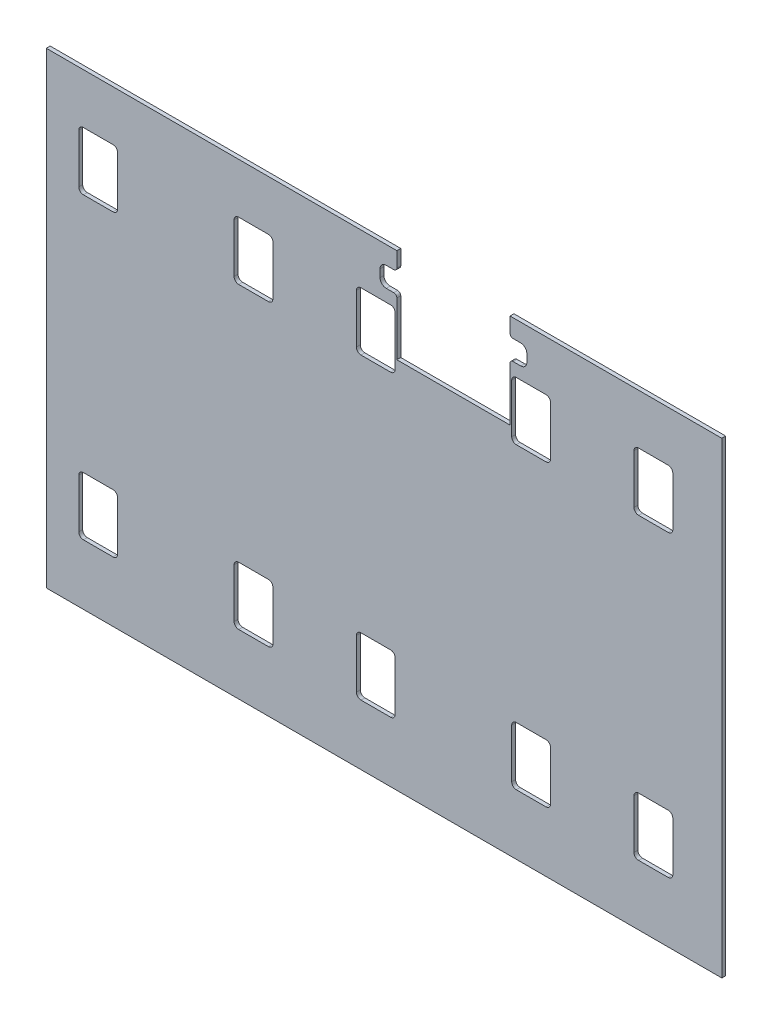
SolidWorks part; units mm, degrees
material "PP Film"
ref_plane "X-Y Datum" through (0, 0, 0) normal (0, 0, 1) x (1, 0, 0)
ref_plane "X-Z Datum" through (0, 0, 0) normal (0, 1, 0) x (1, 0, 0)
ref_plane "Y-Z Datum" through (0, 0, 0) normal (1, 0, 0) x (0, 0, -1)
sketch "Sketch1" plane through (0, 0, 0) normal (0, 0, 1) x (1, 0, 0)
  line L0 (-177.3154, 116.8) -> (-196.7154, 116.8) construction
  line L1 (-199.7154, 113.8) -> (-199.7154, 81.7) construction
  line L2 (-174.3154, 81.7) -> (-174.3154, 113.8) construction
  line L3 (-196.7154, 78.7) -> (-177.3154, 78.7) construction
  line L4 (-220.9897, 149.5877) -> (-220.9897, -156.2291)
  line L5 (-220.9897, -156.2291) -> (220.9897, -156.2291)
  line L6 (220.9897, -156.2291) -> (220.9897, 149.5877)
  line L7 (220.9897, 149.5877) -> (-220.9897, 149.5877)
  line L8 (-220.9897, 149.5877) -> (-220.9897, -156.2291)
  line L9 (-220.9897, -156.2291) -> (220.9897, -156.2291)
  line L10 (220.9897, -156.2291) -> (220.9897, 149.5877)
  line L11 (220.9897, 149.5877) -> (-220.9897, 149.5877)
  line L12 (-177.3154, 116.8) -> (-196.7154, 116.8)
  line L13 (-199.7154, 113.8) -> (-199.7154, 81.7)
  line L14 (-174.3154, 81.7) -> (-174.3154, 113.8)
  line L15 (-196.7154, 78.7) -> (-177.3154, 78.7)
  line L16 (-174.3154, -81.7) -> (-174.3154, -113.8) construction
  line L18 (-196.7154, -78.7) -> (-177.3154, -78.7) construction
  line L19 (-199.7154, -113.8) -> (-199.7154, -81.7) construction
  line L20 (-177.3154, -116.8) -> (-196.7154, -116.8) construction
  line L21 (-199.7154, -113.8) -> (-199.7154, -81.7)
  line L22 (-196.7154, -78.7) -> (-177.3154, -78.7)
  line L23 (-174.3154, -81.7) -> (-174.3154, -113.8)
  line L24 (-177.3154, -116.8) -> (-196.7154, -116.8)
  line L25 (-75.7126, 116.8) -> (-95.1126, 116.8) construction
  line L26 (-95.1126, 78.7) -> (-75.7126, 78.7) construction
  line L27 (-98.1126, 113.8) -> (-98.1126, 81.7) construction
  line L28 (-72.7126, 81.7) -> (-72.7126, 113.8) construction
  line L29 (-75.7126, 116.8) -> (-95.1126, 116.8)
  line L30 (-95.1126, 78.7) -> (-75.7126, 78.7)
  line L31 (-98.1126, 113.8) -> (-98.1126, 81.7)
  line L32 (-72.7126, 81.7) -> (-72.7126, 113.8)
  line L33 (-95.1126, -78.7) -> (-75.7126, -78.7) construction
  line L34 (-72.7126, -81.7) -> (-72.7126, -113.8) construction
  line L35 (-98.1126, -113.8) -> (-98.1126, -81.7) construction
  line L36 (-75.7126, -116.8) -> (-95.1126, -116.8) construction
  line L37 (-95.1126, -78.7) -> (-75.7126, -78.7)
  line L38 (-72.7126, -81.7) -> (-72.7126, -113.8)
  line L39 (-98.1126, -113.8) -> (-98.1126, -81.7)
  line L40 (-75.7126, -116.8) -> (-95.1126, -116.8)
  arc A0 (-174.3154, 113.8) -> (-177.3154, 116.8) centre (-177.3154, 113.8) ccw construction
  arc A1 (-196.7154, 116.8) -> (-199.7154, 113.8) centre (-196.7154, 113.8) ccw construction
  arc A2 (-177.3154, 78.7) -> (-174.3154, 81.7) centre (-177.3154, 81.7) ccw construction
  arc A3 (-199.7154, 81.7) -> (-196.7154, 78.7) centre (-196.7154, 81.7) ccw construction
  arc A4 (-174.3154, 113.8) -> (-177.3154, 116.8) centre (-177.3154, 113.8) ccw
  arc A5 (-196.7154, 116.8) -> (-199.7154, 113.8) centre (-196.7154, 113.8) ccw
  arc A6 (-177.3154, 78.7) -> (-174.3154, 81.7) centre (-177.3154, 81.7) ccw
  arc A7 (-199.7154, 81.7) -> (-196.7154, 78.7) centre (-196.7154, 81.7) ccw
  arc A8 (-174.3154, -81.7) -> (-177.3154, -78.7) centre (-177.3154, -81.7) ccw construction
  arc A9 (-196.7154, -78.7) -> (-199.7154, -81.7) centre (-196.7154, -81.7) ccw construction
  arc A10 (-177.3154, -116.8) -> (-174.3154, -113.8) centre (-177.3154, -113.8) ccw construction
  arc A11 (-199.7154, -113.8) -> (-196.7154, -116.8) centre (-196.7154, -113.8) ccw construction
  arc A12 (-196.7154, -78.7) -> (-199.7154, -81.7) centre (-196.7154, -81.7) ccw
  arc A13 (-174.3154, -81.7) -> (-177.3154, -78.7) centre (-177.3154, -81.7) ccw
  arc A14 (-177.3154, -116.8) -> (-174.3154, -113.8) centre (-177.3154, -113.8) ccw
  arc A15 (-199.7154, -113.8) -> (-196.7154, -116.8) centre (-196.7154, -113.8) ccw
  arc A16 (-72.7126, 113.8) -> (-75.7126, 116.8) centre (-75.7126, 113.8) ccw construction
  arc A17 (-95.1126, 116.8) -> (-98.1126, 113.8) centre (-95.1126, 113.8) ccw construction
  arc A18 (-75.7126, 78.7) -> (-72.7126, 81.7) centre (-75.7126, 81.7) ccw construction
  arc A19 (-98.1126, 81.7) -> (-95.1126, 78.7) centre (-95.1126, 81.7) ccw construction
  arc A20 (-72.7126, 113.8) -> (-75.7126, 116.8) centre (-75.7126, 113.8) ccw
  arc A21 (-95.1126, 116.8) -> (-98.1126, 113.8) centre (-95.1126, 113.8) ccw
  arc A22 (-75.7126, 78.7) -> (-72.7126, 81.7) centre (-75.7126, 81.7) ccw
  arc A23 (-98.1126, 81.7) -> (-95.1126, 78.7) centre (-95.1126, 81.7) ccw
  arc A24 (-72.7126, -81.7) -> (-75.7126, -78.7) centre (-75.7126, -81.7) ccw construction
  arc A25 (-95.1126, -78.7) -> (-98.1126, -81.7) centre (-95.1126, -81.7) ccw construction
  arc A26 (-75.7126, -116.8) -> (-72.7126, -113.8) centre (-75.7126, -113.8) ccw construction
  arc A27 (-98.1126, -113.8) -> (-95.1126, -116.8) centre (-95.1126, -113.8) ccw construction
  arc A28 (-72.7126, -81.7) -> (-75.7126, -78.7) centre (-75.7126, -81.7) ccw
  arc A29 (-95.1126, -78.7) -> (-98.1126, -81.7) centre (-95.1126, -81.7) ccw
  arc A30 (-75.7126, -116.8) -> (-72.7126, -113.8) centre (-75.7126, -113.8) ccw
  arc A31 (-98.1126, -113.8) -> (-95.1126, -116.8) centre (-95.1126, -113.8) ccw
  dimension "D1" = 0
extrude "Boss-Extrude1" add sketch "Sketch1" along normal blind 2.54 contours L10 L11 L8 L9 A31 L39 A29 L37 A28 L38 A30 L40 A23 L31 A21 L29 A20 L32 A22 L30 A15 L21 A12 L22 A13 L23 A14 L24 A7 L13 A5 L12 A4 L14 A6 L15 | L21 A15 L24 A14 L23 A13 L22 A12 | L39 A31 L40 A30 L38 A28 L37 A29 | L13 A7 L15 A6 L14 A4 L12 A5 | L31 A23 L30 A22 L32 A20 L29 A21
sketch "Sketch2" plane through (0, 0, 2.54) normal (0, 0, 1) x (1, 0, 0)
  line L4 (-220.9897, 149.5877) -> (-220.9897, -156.2291)
  line L5 (-220.9897, -156.2291) -> (220.9897, -156.2291)
  line L6 (220.9897, -156.2291) -> (220.9897, 149.5877)
  line L7 (220.9897, 149.5877) -> (-220.9897, 149.5877)
  line L8 (-220.9897, 149.5877) -> (-220.9897, -156.2291)
  line L9 (-220.9897, -156.2291) -> (220.9897, -156.2291)
  line L10 (220.9897, -156.2291) -> (220.9897, 149.5877)
  line L11 (220.9897, 149.5877) -> (-220.9897, 149.5877)
  line L12 (-199.7154, -81.7) -> (-199.7154, -113.8)
  line L13 (-177.3154, -78.7) -> (-196.7154, -78.7)
  line L14 (-174.3154, -113.8) -> (-174.3154, -81.7)
  line L15 (-196.7154, -116.8) -> (-177.3154, -116.8)
  line L16 (-199.7154, -81.7) -> (-199.7154, -113.8)
  line L17 (-177.3154, -78.7) -> (-196.7154, -78.7)
  line L18 (-174.3154, -113.8) -> (-174.3154, -81.7)
  line L19 (-196.7154, -116.8) -> (-177.3154, -116.8)
  line L20 (-199.7154, 113.8) -> (-199.7154, 81.7)
  line L21 (-177.3154, 116.8) -> (-196.7154, 116.8)
  line L22 (-174.3154, 81.7) -> (-174.3154, 113.8)
  line L23 (-196.7154, 78.7) -> (-177.3154, 78.7)
  line L24 (-199.7154, 113.8) -> (-199.7154, 81.7)
  line L25 (-177.3154, 116.8) -> (-196.7154, 116.8)
  line L26 (-174.3154, 81.7) -> (-174.3154, 113.8)
  line L27 (-196.7154, 78.7) -> (-177.3154, 78.7)
  line L28 (-75.7126, 116.8) -> (-95.1126, 116.8)
  line L29 (-72.7126, 81.7) -> (-72.7126, 113.8)
  line L30 (-95.1126, 78.7) -> (-75.7126, 78.7)
  line L31 (-98.1126, 113.8) -> (-98.1126, 81.7)
  line L32 (-75.7126, 116.8) -> (-95.1126, 116.8)
  line L33 (-72.7126, 81.7) -> (-72.7126, 113.8)
  line L34 (-95.1126, 78.7) -> (-75.7126, 78.7)
  line L35 (-98.1126, 113.8) -> (-98.1126, 81.7)
  line L36 (-95.1126, -116.8) -> (-75.7126, -116.8)
  line L37 (-72.7126, -113.8) -> (-72.7126, -81.7)
  line L38 (-75.7126, -78.7) -> (-95.1126, -78.7)
  line L39 (-98.1126, -81.7) -> (-98.1126, -113.8)
  line L40 (-95.1126, -116.8) -> (-75.7126, -116.8)
  line L41 (-72.7126, -113.8) -> (-72.7126, -81.7)
  line L42 (-75.7126, -78.7) -> (-95.1126, -78.7)
  line L43 (-98.1126, -81.7) -> (-98.1126, -113.8)
  arc A4 (-196.7154, -78.7) -> (-199.7154, -81.7) centre (-196.7154, -81.7) ccw
  arc A5 (-174.3154, -81.7) -> (-177.3154, -78.7) centre (-177.3154, -81.7) ccw
  arc A6 (-177.3154, -116.8) -> (-174.3154, -113.8) centre (-177.3154, -113.8) ccw
  arc A7 (-199.7154, -113.8) -> (-196.7154, -116.8) centre (-196.7154, -113.8) ccw
  arc A8 (-196.7154, -78.7) -> (-199.7154, -81.7) centre (-196.7154, -81.7) ccw
  arc A9 (-174.3154, -81.7) -> (-177.3154, -78.7) centre (-177.3154, -81.7) ccw
  arc A10 (-177.3154, -116.8) -> (-174.3154, -113.8) centre (-177.3154, -113.8) ccw
  arc A11 (-199.7154, -113.8) -> (-196.7154, -116.8) centre (-196.7154, -113.8) ccw
  arc A12 (-199.7154, 81.7) -> (-196.7154, 78.7) centre (-196.7154, 81.7) ccw
  arc A13 (-196.7154, 116.8) -> (-199.7154, 113.8) centre (-196.7154, 113.8) ccw
  arc A14 (-174.3154, 113.8) -> (-177.3154, 116.8) centre (-177.3154, 113.8) ccw
  arc A15 (-177.3154, 78.7) -> (-174.3154, 81.7) centre (-177.3154, 81.7) ccw
  arc A16 (-199.7154, 81.7) -> (-196.7154, 78.7) centre (-196.7154, 81.7) ccw
  arc A17 (-196.7154, 116.8) -> (-199.7154, 113.8) centre (-196.7154, 113.8) ccw
  arc A18 (-174.3154, 113.8) -> (-177.3154, 116.8) centre (-177.3154, 113.8) ccw
  arc A19 (-177.3154, 78.7) -> (-174.3154, 81.7) centre (-177.3154, 81.7) ccw
  arc A20 (-72.7126, 113.8) -> (-75.7126, 116.8) centre (-75.7126, 113.8) ccw
  arc A21 (-75.7126, 78.7) -> (-72.7126, 81.7) centre (-75.7126, 81.7) ccw
  arc A22 (-98.1126, 81.7) -> (-95.1126, 78.7) centre (-95.1126, 81.7) ccw
  arc A23 (-95.1126, 116.8) -> (-98.1126, 113.8) centre (-95.1126, 113.8) ccw
  arc A24 (-72.7126, 113.8) -> (-75.7126, 116.8) centre (-75.7126, 113.8) ccw
  arc A25 (-75.7126, 78.7) -> (-72.7126, 81.7) centre (-75.7126, 81.7) ccw
  arc A26 (-98.1126, 81.7) -> (-95.1126, 78.7) centre (-95.1126, 81.7) ccw
  arc A27 (-95.1126, 116.8) -> (-98.1126, 113.8) centre (-95.1126, 113.8) ccw
  arc A28 (-98.1126, -113.8) -> (-95.1126, -116.8) centre (-95.1126, -113.8) ccw
  arc A29 (-75.7126, -116.8) -> (-72.7126, -113.8) centre (-75.7126, -113.8) ccw
  arc A30 (-72.7126, -81.7) -> (-75.7126, -78.7) centre (-75.7126, -81.7) ccw
  arc A31 (-95.1126, -78.7) -> (-98.1126, -81.7) centre (-95.1126, -81.7) ccw
  arc A32 (-98.1126, -113.8) -> (-95.1126, -116.8) centre (-95.1126, -113.8) ccw
  arc A33 (-75.7126, -116.8) -> (-72.7126, -113.8) centre (-75.7126, -113.8) ccw
  arc A34 (-72.7126, -81.7) -> (-75.7126, -78.7) centre (-75.7126, -81.7) ccw
  arc A35 (-95.1126, -78.7) -> (-98.1126, -81.7) centre (-95.1126, -81.7) ccw
  dimension "D1" = 0
  dimension "D2" = 0
  dimension "D3" = 0
  dimension "D4" = 0
  dimension "D5" = 0
extrude "Cut-Extrude1" cut sketch "Sketch2" against normal through all contours L27 A19 L26 A18 L25 A17 L24 A16 | L16 A11 L19 A10 L18 A9 L17 A8
pattern_linear "LPattern1" count 3 spacing 181.614 along (1, 0, 0) of "Cut-Extrude1"
sketch "Sketch3" plane through (0, 0, 2.54) normal (0, 0, 1) x (1, 0, 0)
  line L4 (-220.9897, 149.5877) -> (-220.9897, -156.2291)
  line L5 (-220.9897, -156.2291) -> (220.9897, -156.2291)
  line L6 (220.9897, -156.2291) -> (220.9897, 149.5877)
  line L7 (220.9897, 149.5877) -> (-220.9897, 149.5877)
  line L8 (-220.9897, 149.5877) -> (-220.9897, -156.2291)
  line L9 (-220.9897, -156.2291) -> (220.9897, -156.2291)
  line L10 (220.9897, -156.2291) -> (220.9897, 149.5877)
  line L11 (220.9897, 149.5877) -> (-220.9897, 149.5877)
  line L12 (-196.7154, -116.8) -> (-177.3154, -116.8)
  line L13 (-174.3154, -113.8) -> (-174.3154, -81.7)
  line L14 (-177.3154, -78.7) -> (-196.7154, -78.7)
  line L15 (-199.7154, -81.7) -> (-199.7154, -113.8)
  line L16 (-196.7154, -116.8) -> (-177.3154, -116.8)
  line L17 (-174.3154, -113.8) -> (-174.3154, -81.7)
  line L18 (-177.3154, -78.7) -> (-196.7154, -78.7)
  line L19 (-199.7154, -81.7) -> (-199.7154, -113.8)
  line L20 (-95.1126, 78.7) -> (-75.7126, 78.7)
  line L21 (-98.1126, 113.8) -> (-98.1126, 81.7)
  line L22 (-75.7126, 116.8) -> (-95.1126, 116.8)
  line L23 (-72.7126, 81.7) -> (-72.7126, 113.8)
  line L24 (-95.1126, 78.7) -> (-75.7126, 78.7)
  line L25 (-98.1126, 113.8) -> (-98.1126, 81.7)
  line L26 (-75.7126, 116.8) -> (-95.1126, 116.8)
  line L27 (-72.7126, 81.7) -> (-72.7126, 113.8)
  line L28 (-196.7154, 78.7) -> (-177.3154, 78.7)
  line L29 (-199.7154, 113.8) -> (-199.7154, 81.7)
  line L30 (-177.3154, 116.8) -> (-196.7154, 116.8)
  line L31 (-174.3154, 81.7) -> (-174.3154, 113.8)
  line L32 (-196.7154, 78.7) -> (-177.3154, 78.7)
  line L33 (-199.7154, 113.8) -> (-199.7154, 81.7)
  line L34 (-177.3154, 116.8) -> (-196.7154, 116.8)
  line L35 (-174.3154, 81.7) -> (-174.3154, 113.8)
  line L36 (-72.7126, -113.8) -> (-72.7126, -81.7)
  line L37 (-95.1126, -116.8) -> (-75.7126, -116.8)
  line L38 (-98.1126, -81.7) -> (-98.1126, -113.8)
  line L39 (-75.7126, -78.7) -> (-95.1126, -78.7)
  line L40 (-72.7126, -113.8) -> (-72.7126, -81.7)
  line L41 (-95.1126, -116.8) -> (-75.7126, -116.8)
  line L42 (-98.1126, -81.7) -> (-98.1126, -113.8)
  line L43 (-75.7126, -78.7) -> (-95.1126, -78.7)
  arc A4 (-177.3154, -116.8) -> (-174.3154, -113.8) centre (-177.3154, -113.8) ccw
  arc A5 (-174.3154, -81.7) -> (-177.3154, -78.7) centre (-177.3154, -81.7) ccw
  arc A6 (-196.7154, -78.7) -> (-199.7154, -81.7) centre (-196.7154, -81.7) ccw
  arc A7 (-199.7154, -113.8) -> (-196.7154, -116.8) centre (-196.7154, -113.8) ccw
  arc A8 (-177.3154, -116.8) -> (-174.3154, -113.8) centre (-177.3154, -113.8) ccw
  arc A9 (-174.3154, -81.7) -> (-177.3154, -78.7) centre (-177.3154, -81.7) ccw
  arc A10 (-196.7154, -78.7) -> (-199.7154, -81.7) centre (-196.7154, -81.7) ccw
  arc A11 (-199.7154, -113.8) -> (-196.7154, -116.8) centre (-196.7154, -113.8) ccw
  arc A12 (-75.7126, 78.7) -> (-72.7126, 81.7) centre (-75.7126, 81.7) ccw
  arc A13 (-98.1126, 81.7) -> (-95.1126, 78.7) centre (-95.1126, 81.7) ccw
  arc A14 (-95.1126, 116.8) -> (-98.1126, 113.8) centre (-95.1126, 113.8) ccw
  arc A15 (-72.7126, 113.8) -> (-75.7126, 116.8) centre (-75.7126, 113.8) ccw
  arc A16 (-75.7126, 78.7) -> (-72.7126, 81.7) centre (-75.7126, 81.7) ccw
  arc A17 (-98.1126, 81.7) -> (-95.1126, 78.7) centre (-95.1126, 81.7) ccw
  arc A18 (-95.1126, 116.8) -> (-98.1126, 113.8) centre (-95.1126, 113.8) ccw
  arc A19 (-72.7126, 113.8) -> (-75.7126, 116.8) centre (-75.7126, 113.8) ccw
  arc A20 (-199.7154, 81.7) -> (-196.7154, 78.7) centre (-196.7154, 81.7) ccw
  arc A21 (-196.7154, 116.8) -> (-199.7154, 113.8) centre (-196.7154, 113.8) ccw
  arc A22 (-174.3154, 113.8) -> (-177.3154, 116.8) centre (-177.3154, 113.8) ccw
  arc A23 (-177.3154, 78.7) -> (-174.3154, 81.7) centre (-177.3154, 81.7) ccw
  arc A24 (-199.7154, 81.7) -> (-196.7154, 78.7) centre (-196.7154, 81.7) ccw
  arc A25 (-196.7154, 116.8) -> (-199.7154, 113.8) centre (-196.7154, 113.8) ccw
  arc A26 (-174.3154, 113.8) -> (-177.3154, 116.8) centre (-177.3154, 113.8) ccw
  arc A27 (-177.3154, 78.7) -> (-174.3154, 81.7) centre (-177.3154, 81.7) ccw
  arc A28 (-75.7126, -116.8) -> (-72.7126, -113.8) centre (-75.7126, -113.8) ccw
  arc A29 (-98.1126, -113.8) -> (-95.1126, -116.8) centre (-95.1126, -113.8) ccw
  arc A30 (-95.1126, -78.7) -> (-98.1126, -81.7) centre (-95.1126, -81.7) ccw
  arc A31 (-72.7126, -81.7) -> (-75.7126, -78.7) centre (-75.7126, -81.7) ccw
  arc A32 (-75.7126, -116.8) -> (-72.7126, -113.8) centre (-75.7126, -113.8) ccw
  arc A33 (-98.1126, -113.8) -> (-95.1126, -116.8) centre (-95.1126, -113.8) ccw
  arc A34 (-95.1126, -78.7) -> (-98.1126, -81.7) centre (-95.1126, -81.7) ccw
  arc A35 (-72.7126, -81.7) -> (-75.7126, -78.7) centre (-75.7126, -81.7) ccw
  dimension "D1" = 0
  dimension "D2" = 0
  dimension "D3" = 0
  dimension "D4" = 0
  dimension "D5" = 0
extrude "Cut-Extrude2" cut sketch "Sketch3" against normal through all contours L27 A19 L26 A18 L25 A17 L24 A16 | L40 A35 L43 A34 L42 A33 L41 A32
pattern_linear "LPattern2" count 2 spacing 181.614 along (1, 0, 0) of "Cut-Extrude2"
sketch "Sketch5" plane through (0, 0, 2.54) normal (0, 0, 1) x (1, 0, 0)
  line L0 (79.4, 88.7877) -> (81.4, 88.7877) construction
  line L1 (81.4, 88.7877) -> (81.4, 148.7877) construction
  line L2 (81.4, 148.7877) -> (79.4, 148.7877) construction
  line L3 (79.4, 148.7877) -> (79.4, 88.7877) construction
  line L4 (6.4, 136.7877) -> (1.4, 136.7877)
  line L5 (-1.6, 133.7877) -> (-1.6, 128.7877)
  line L6 (1.4, 125.7877) -> (6.4, 125.7877)
  line L7 (9.4, 122.7877) -> (9.4, 139.7877)
  line L8 (6.4, 136.7877) -> (1.4, 136.7877) construction
  line L9 (-1.6, 133.7877) -> (-1.6, 128.7877) construction
  line L10 (1.4, 125.7877) -> (6.4, 125.7877) construction
  line L11 (9.4, 122.7877) -> (9.4, 139.7877) construction
  line L12 (84.4, 125.7877) -> (89.4, 125.7877)
  line L13 (92.4, 128.7877) -> (92.4, 133.7877)
  line L14 (89.4, 136.7877) -> (84.4, 136.7877)
  line L15 (81.4, 139.7877) -> (81.4, 122.7877)
  line L16 (84.4, 125.7877) -> (89.4, 125.7877) construction
  line L17 (92.4, 128.7877) -> (92.4, 133.7877) construction
  line L18 (89.4, 136.7877) -> (84.4, 136.7877) construction
  line L19 (81.4, 139.7877) -> (81.4, 122.7877) construction
  line L20 (11.4, 88.7877) -> (79.4, 88.7877) construction
  line L21 (79.4, 88.7877) -> (79.4, 148.7877) construction
  line L22 (79.4, 148.7877) -> (11.4, 148.7877) construction
  line L23 (11.4, 148.7877) -> (11.4, 88.7877) construction
  line L24 (9.4, 88.7877) -> (11.4, 88.7877) construction
  line L25 (11.4, 88.7877) -> (11.4, 148.7877) construction
  line L26 (11.4, 148.7877) -> (9.4, 148.7877) construction
  line L27 (9.4, 148.7877) -> (9.4, 88.7877) construction
  line L28 (79.4, 88.7877) -> (81.4, 88.7877) construction
  line L29 (81.4, 88.7877) -> (81.4, 148.7877) construction
  line L30 (81.4, 148.7877) -> (79.4, 148.7877) construction
  line L31 (79.4, 148.7877) -> (79.4, 88.7877) construction
  line L32 (11.4, 88.7877) -> (79.4, 88.7877) construction
  line L33 (79.4, 88.7877) -> (79.4, 148.7877) construction
  line L34 (79.4, 148.7877) -> (11.4, 148.7877) construction
  line L35 (11.4, 148.7877) -> (11.4, 88.7877) construction
  line L36 (9.4, 88.7877) -> (11.4, 88.7877) construction
  line L37 (11.4, 88.7877) -> (11.4, 148.7877) construction
  line L38 (11.4, 148.7877) -> (9.4, 148.7877) construction
  line L39 (9.4, 148.7877) -> (9.4, 88.7877) construction
  line L40 (82.416, 149.8037) -> (8.384, 149.8037)
  line L41 (8.384, 149.8037) -> (8.384, 87.7717)
  line L42 (8.384, 87.7717) -> (11.4, 87.7717)
  line L43 (11.4, 87.7717) -> (79.4, 87.7717)
  line L44 (11.4, 88.7877) -> (79.4, 88.7877)
  line L45 (79.4, 88.7877) -> (79.4, 148.7877)
  line L46 (79.4, 148.7877) -> (11.4, 148.7877)
  line L47 (11.4, 148.7877) -> (11.4, 88.7877)
  line L48 (11.4, 88.7877) -> (79.4, 88.7877) construction
  line L49 (79.4, 88.7877) -> (79.4, 148.7877) construction
  line L50 (79.4, 148.7877) -> (11.4, 148.7877) construction
  line L51 (11.4, 148.7877) -> (11.4, 88.7877) construction
  line L52 (79.4, 87.7717) -> (82.416, 87.7717)
  line L53 (82.416, 87.7717) -> (82.416, 149.8037)
  line L54 (84.4, 124.7717) -> (89.4, 124.7717)
  line L55 (93.416, 128.7877) -> (93.416, 133.7877)
  line L56 (89.4, 137.8037) -> (84.4, 137.8037)
  line L57 (1.4, 124.7717) -> (6.4, 124.7717)
  line L58 (-2.616, 133.7877) -> (-2.616, 128.7877)
  line L59 (6.4, 137.8037) -> (1.4, 137.8037)
  line L60 (11.4, 149.8037) -> (8.384, 149.8037) construction
  line L62 (82.416, 87.7717) -> (82.416, 148.7877) construction
  arc A0 (84.4, 124.7717) -> (82.416, 122.7877) centre (84.4, 122.7877) ccw
  arc A1 (89.4, 124.7717) -> (93.416, 128.7877) centre (89.4, 128.7877) ccw
  arc A2 (93.416, 133.7877) -> (89.4, 137.8037) centre (89.4, 133.7877) ccw
  arc A3 (82.416, 139.7877) -> (84.4, 137.8037) centre (84.4, 139.7877) ccw
  arc A4 (1.4, 136.7877) -> (-1.6, 133.7877) centre (1.4, 133.7877) ccw
  arc A5 (-1.6, 128.7877) -> (1.4, 125.7877) centre (1.4, 128.7877) ccw
  arc A6 (9.4, 122.7877) -> (6.4, 125.7877) centre (6.4, 122.7877) ccw
  arc A7 (6.4, 136.7877) -> (9.4, 139.7877) centre (6.4, 139.7877) ccw
  arc A8 (1.4, 136.7877) -> (-1.6, 133.7877) centre (1.4, 133.7877) ccw construction
  arc A9 (-1.6, 128.7877) -> (1.4, 125.7877) centre (1.4, 128.7877) ccw construction
  arc A10 (9.4, 122.7877) -> (6.4, 125.7877) centre (6.4, 122.7877) ccw construction
  arc A11 (6.4, 136.7877) -> (9.4, 139.7877) centre (6.4, 139.7877) ccw construction
  arc A12 (89.4, 125.7877) -> (92.4, 128.7877) centre (89.4, 128.7877) ccw
  arc A13 (92.4, 133.7877) -> (89.4, 136.7877) centre (89.4, 133.7877) ccw
  arc A14 (81.4, 139.7877) -> (84.4, 136.7877) centre (84.4, 139.7877) ccw
  arc A15 (84.4, 125.7877) -> (81.4, 122.7877) centre (84.4, 122.7877) ccw
  arc A16 (89.4, 125.7877) -> (92.4, 128.7877) centre (89.4, 128.7877) ccw construction
  arc A17 (92.4, 133.7877) -> (89.4, 136.7877) centre (89.4, 133.7877) ccw construction
  arc A18 (81.4, 139.7877) -> (84.4, 136.7877) centre (84.4, 139.7877) ccw construction
  arc A19 (84.4, 125.7877) -> (81.4, 122.7877) centre (84.4, 122.7877) ccw construction
  arc A20 (8.384, 122.7877) -> (6.4, 124.7717) centre (6.4, 122.7877) ccw
  arc A21 (-2.616, 128.7877) -> (1.4, 124.7717) centre (1.4, 128.7877) ccw
  arc A22 (1.4, 137.8037) -> (-2.616, 133.7877) centre (1.4, 133.7877) ccw
  arc A23 (6.4, 137.8037) -> (8.384, 139.7877) centre (6.4, 139.7877) ccw
  point P67 (27.8601, 149.8037)
  point P69 (74.8585, 149.5877)
  point P70 (82.416, 149.8037)
  point P72 (82.2483, 149.8037)
  dimension "D1" = 0
  dimension "D2" = 0
  dimension "D3" = 0
  dimension "D4" = 1.016
  dimension "D5" = 1.016
  dimension "D6" = 1.016
extrude "Cut-Extrude3" cut sketch "Sketch5" against normal through all contours L52 L53 L40 L41 L42 L43 | A3 L53 A0 L54 A1 L55 A2 L56 | A23 L59 A22 L58 A21 L57 A20 L41
